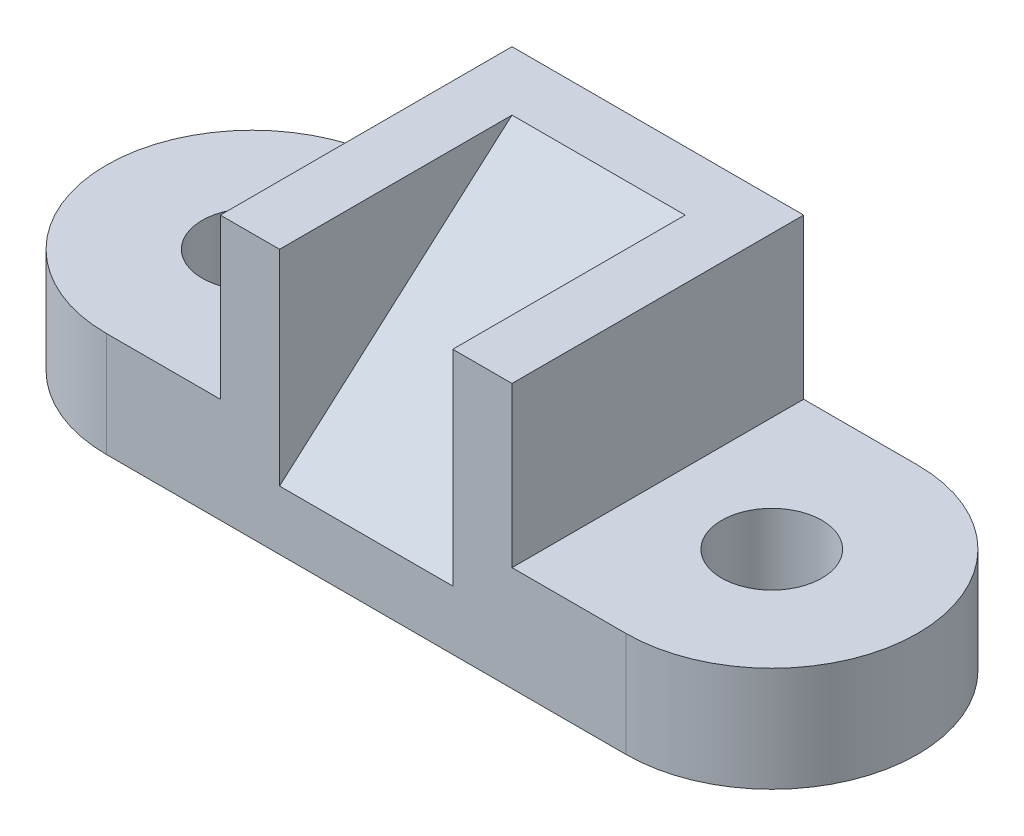
SolidWorks part; units mm, degrees
ref_plane "Front Plane" through (0, 0, 0) normal (0, 0, 1) x (1, 0, 0)
ref_plane "Top Plane" through (0, 0, 0) normal (0, 1, 0) x (1, 0, 0)
ref_plane "Right Plane" through (0, 0, 0) normal (1, 0, 0) x (0, 0, -1)
sketch "Sketch1" plane through (0, 0, 0) normal (0, 1, 0) x (1, 0, 0)
  line L0 (-57, 0) -> (57, 0) construction
  line L1 (-57, 32) -> (57, 32)
  line L2 (-57, -32) -> (57, -32)
  line L3 (0, 32) -> (0, -32) construction
  arc A0 (-57, 32) -> (-57, -32) centre (-57, 0) ccw
  arc A1 (57, -32) -> (57, 32) centre (57, 0) ccw
  circle A2 centre (-57, 0) radius 11
  circle A3 centre (57, 0) radius 11
  point P2 (0, 0)
  point P13 (0, 0)
  dimension "D3" = 22
  dimension "D1" = 64
  dimension "D2" = 114
extrude "Boss-Extrude2" add sketch "Sketch1" along normal blind 13
sketch "Sketch4" plane through (0, 13, 0) normal (0, 1, 0) x (1, 0, 0)
  line L6 (0, 32) -> (0, -32) construction
  line L7 (-57, -32) -> (57, -32) construction
  line L8 (57, 32) -> (-57, 32) construction
  line L9 (-19, -32) -> (19, -32)
  line L10 (-19, -32) -> (-19, 19)
  line L11 (-19, 19) -> (19, 19)
  line L12 (19, -32) -> (19, 19)
  point P5 (0, 0)
  dimension "D1" = 13
  dimension "D2" = 38
extrude "Boss-Extrude3" add sketch "Sketch4" along normal blind 45
sketch "Sketch5" plane through (19, 0, 0) normal (1, 0, 0) x (0, 0, -1)
  line L0 (19, 58) -> (-32, 13)
  line L1 (-32, 13) -> (-32, 58)
  line L2 (-32, 58) -> (19, 58)
extrude "Cut-Extrude1" cut sketch "Sketch5" against normal blind 45
sketch "Sketch6" plane through (0, 13, 0) normal (0, 1, 0) x (1, 0, 0)
  line L0 (-32, -32) -> (-32, 32)
  line L1 (-57, -32) -> (-19, -32) construction
  line L2 (57, 32) -> (-57, 32) construction
  line L3 (-32, 32) -> (32, 32)
  line L4 (32, 32) -> (32, -32)
  line L5 (19, -32) -> (57, -32) construction
  line L6 (32, -32) -> (19, -32)
  line L7 (-19, -32) -> (-32, -32)
  line L8 (19, 19) -> (-19, 19) construction
  line L15 (-19, -32) -> (-19, 19)
  line L16 (-19, 19) -> (19, 19)
  line L17 (19, 19) -> (19, -32)
  line L18 (19, -32) -> (57, -32)
  line L19 (57, 32) -> (-57, 32)
  line L20 (-57, -32) -> (-19, -32)
  line L24 (19, -32) -> (57, -32)
  line L25 (57, 32) -> (-57, 32)
  line L26 (-57, -32) -> (-19, -32)
  arc A2 (57, -32) -> (57, 32) centre (57, 0) ccw
  arc A3 (-57, 32) -> (-57, -32) centre (-57, 0) ccw
  arc A4 (57, -32) -> (57, 32) centre (57, 0) ccw
  arc A5 (-57, 32) -> (-57, -32) centre (-57, 0) ccw
  line M12 (-19, -32) -> (-19, 19)
  line M13 (-19, 19) -> (19, 19)
  line M14 (19, 19) -> (19, -32)
  line M15 (19, -32) -> (57, -32)
  line M17 (57, 32) -> (-57, 32)
  line M19 (-57, -32) -> (-19, -32)
  dimension "D1" = 13
  dimension "D2" = 13
  dimension "D3" = 13
  dimension "D4" = 0
extrude "Boss-Extrude4" add sketch "Sketch6" along normal blind 45 contours L4 L0 M17 M19 M12 M13 M14 M15
sketch "Sketch15" plane through (0, 13, 0) normal (0, 1, 0) x (1, 0, 0)
  line L0 (-32, 32) -> (-57, 32)
  line L1 (-32, -32) -> (-32, 32)
  line L2 (-32, -32) -> (-57, -32)
  arc A0 (-57, -32) -> (-57, 32) centre (-57, 0) cw
  circle A1 centre (-57, 0) radius 11
extrude "Boss-Extrude6" add sketch "Sketch15" along normal blind 10
sketch "Sketch16" plane through (0, 13, 0) normal (0, 1, 0) x (1, 0, 0)
  line L0 (32, -32) -> (57, -32)
  line L1 (32, -32) -> (32, 32)
  line L2 (32, 32) -> (57, 32)
  arc A0 (57, 32) -> (57, -32) centre (57, 0) cw
  circle A1 centre (57, 0) radius 11
extrude "Boss-Extrude7" add sketch "Sketch16" along normal blind 10
